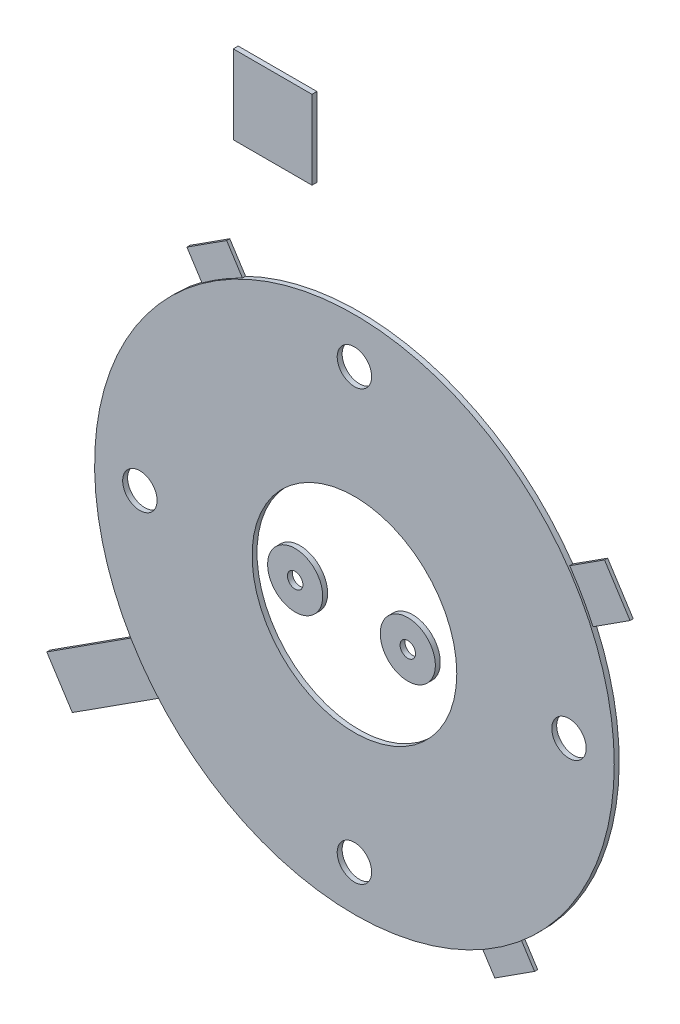
SolidWorks part; units mm, degrees
material "PC High Viscosity"
ref_plane "Front Plane" through (0, 0, 0) normal (0, 0, 1) x (1, 0, 0)
ref_plane "Top Plane" through (0, 0, 0) normal (0, 1, 0) x (1, 0, 0)
ref_plane "Right Plane" through (0, 0, 0) normal (1, 0, 0) x (0, 0, -1)
sketch "Sketch1" plane through (0, 0, 0) normal (0, 0, 1) x (1, 0, 0)
  line L0 (0, -83.82) -> (0, 83.82) construction
  line L1 (-83.82, 0) -> (83.82, 0) construction
  circle A0 centre (0, 0) radius 83.82
  circle A1 centre (0, 0) radius 33.02
  circle A2 centre (-69.215, 0) radius 5.5563
  circle A3 centre (0, 69.215) radius 5.5562
  circle A4 centre (69.215, 0) radius 5.5563
  circle A5 centre (0, -69.215) radius 5.5562
  dimension "D1" = 167.64
  dimension "D2" = 66.04
  dimension "D3" = 138.43
  dimension "D7" = 11.1125
  dimension "D4" = 138.43
  dimension "D5" = 69.215
  dimension "D6" = 69.215
extrude "Boss-Extrude1" add sketch "Sketch1" along normal blind 1.5875
sketch "Sketch2" plane through (0, 0, 0) normal (0, 0, -1) x (-1, 0, 0)
  line L0 (13.6901, 138.4825) -> (39.0901, 138.4825)
  line L1 (13.6901, 138.4825) -> (13.6901, 113.0825)
  line L2 (39.0901, 138.4825) -> (39.0901, 113.0825)
  line L3 (13.6901, 113.0825) -> (39.0901, 113.0825)
  circle A0 centre (-17.2165, -1.138) radius 2.4892
  circle A1 centre (-17.2165, -1.138) radius 8.89
  circle A2 centre (19.1154, 0) radius 2.4892
  circle A3 centre (19.1154, 0) radius 8.89
  dimension "D2" = 17.78
  dimension "D3" = 4.9784
  dimension "D1" = 25.4
extrude "Boss-Extrude2" add sketch "Sketch2" against normal up to surface (1.5875 mm away) separate body up to face at (74.7713, 0, 1.5875)
sketch "Sketch3" plane through (0, 0, 0) normal (0, 0, -1) x (-1, 0, 0)
  line L0 (-58.5933, 41.177) -> (-66.8338, 28.357)
  line L1 (-58.5933, 41.177) -> (-80.105, 55.0043)
  line L2 (-66.8338, 28.357) -> (-88.3454, 42.1842)
  line L3 (-80.105, 55.0043) -> (-88.3454, 42.1842)
  line L4 (-48.5278, -57.2336) -> (-35.7078, -65.474)
  line L5 (-48.5278, -57.2336) -> (-57.5313, -71.2407)
  line L6 (-35.7078, -65.474) -> (-44.7112, -79.4811)
  line L7 (-57.5313, -71.2407) -> (-44.7112, -79.4811)
  line L8 (31.3585, 67.0492) -> (44.1785, 58.8088)
  line L9 (31.3585, 67.0492) -> (41.7966, 83.2883)
  line L10 (44.1785, 58.8088) -> (54.6166, 75.0479)
  line L11 (41.7966, 83.2883) -> (54.6166, 75.0479)
  line L12 (53.9081, -31.1365) -> (45.6677, -43.9565)
  line L13 (53.9081, -31.1365) -> (99.8145, -60.6441)
  line L14 (45.6677, -43.9565) -> (91.574, -73.4641)
  line L15 (99.8145, -60.6441) -> (91.574, -73.4641)
  dimension "D1" = 15.24
extrude "Boss-Extrude3" add sketch "Sketch3" against normal blind 1.016
